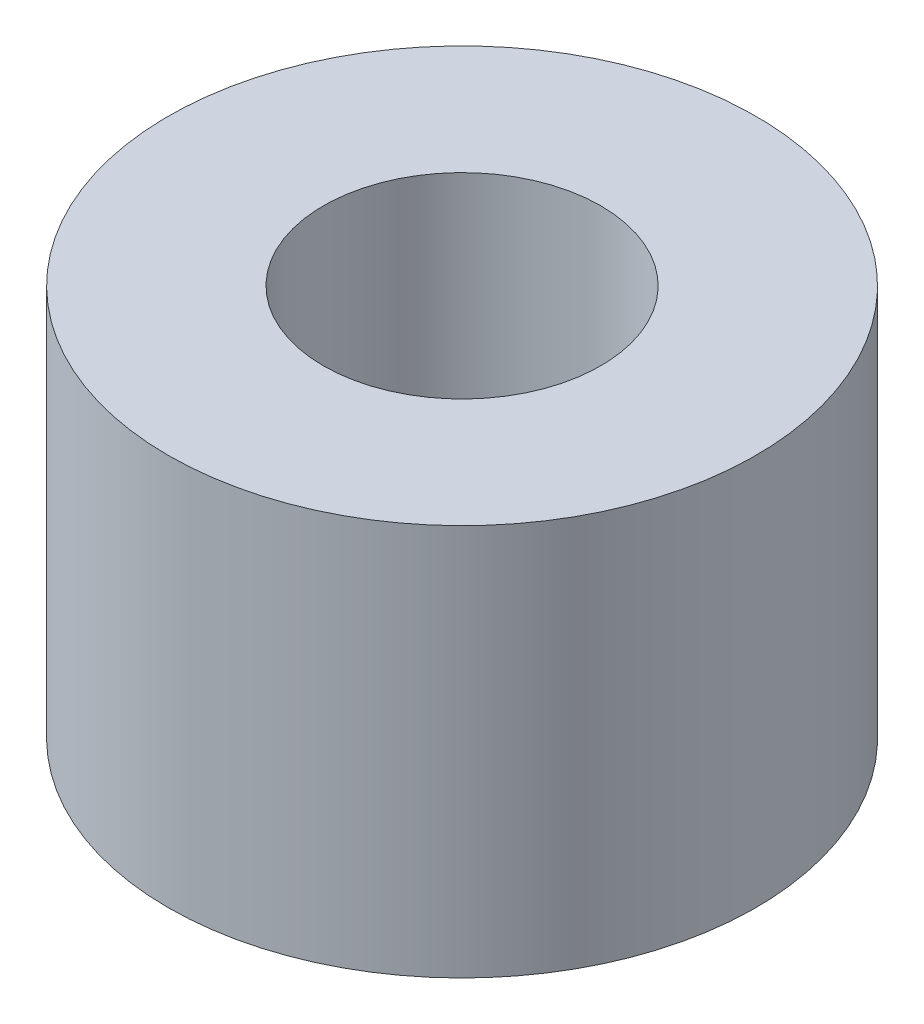
SolidWorks part; units mm, degrees
ref_plane "Front Plane" through (0, 0, 0) normal (0, 0, 1) x (1, 0, 0)
ref_plane "Top Plane" through (0, 0, 0) normal (0, 1, 0) x (1, 0, 0)
ref_plane "Right Plane" through (0, 0, 0) normal (1, 0, 0) x (0, 0, -1)
sketch "Sketch1" plane through (0, 0, 0) normal (0, 1, 0) x (1, 0, 0)
  circle A0 centre (0, 0) radius 2.2479
  circle A1 centre (0, 0) radius 4.7625
  dimension "D1" = 4.4958
  dimension "D2" = 9.525
extrude "Boss-Extrude1" add sketch "Sketch1" along normal blind 6.35 contours A1 A0
